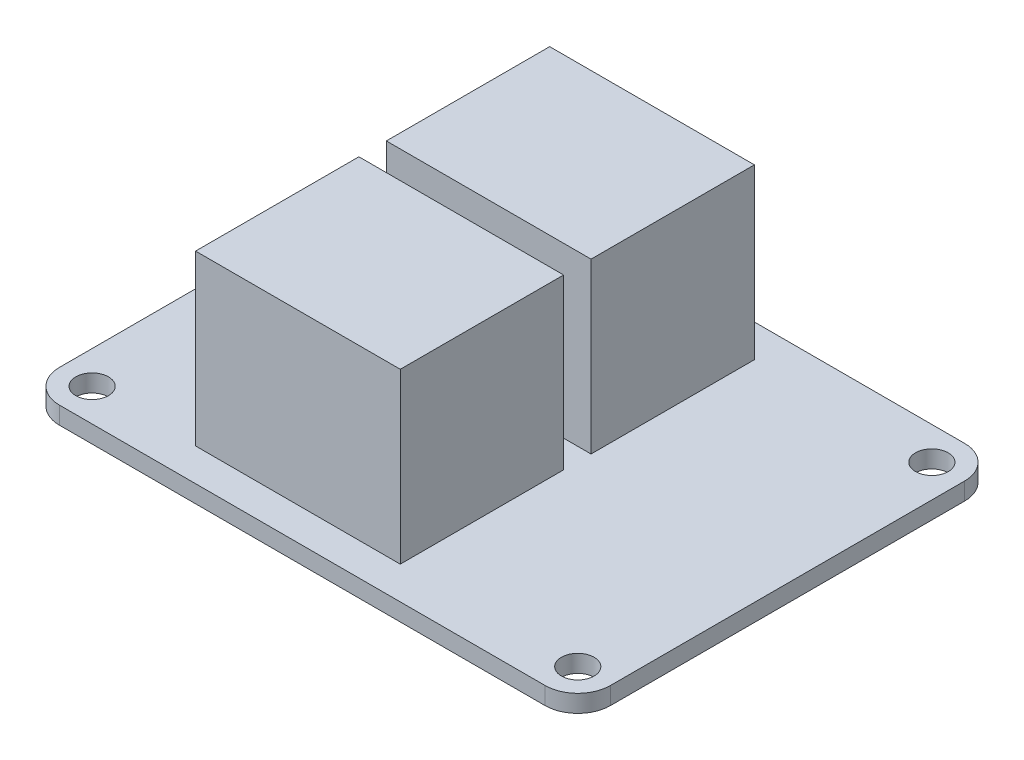
SolidWorks part; units mm, degrees
ref_plane "Front Plane" through (0, 0, 0) normal (0, 0, 1) x (1, 0, 0)
ref_plane "Top Plane" through (0, 0, 0) normal (0, 1, 0) x (1, 0, 0)
ref_plane "Right Plane" through (0, 0, 0) normal (1, 0, 0) x (0, 0, -1)
sketch "Sketch1" plane through (0, 0, 0) normal (0, 1, 0) x (1, 0, 0)
  line L1 (-33.69, 15.154) -> (16.91, 15.154)
  line L2 (-33.69, 15.154) -> (-33.69, -23.366)
  line L3 (-33.69, -23.366) -> (16.91, -23.366)
  line L4 (16.91, 15.154) -> (16.91, -23.366)
  circle A0 centre (13.91, 12.154) radius 1.5
  circle A1 centre (13.91, -20.366) radius 1.5
  circle A2 centre (-30.69, -20.366) radius 1.5
  circle A3 centre (-30.69, 12.154) radius 1.5
  dimension "D3" = 3
  dimension "D4" = 3
  dimension "D5" = 3
  dimension "D6" = 3
  dimension "D7" = 3
  dimension "D8" = 3
  dimension "D9" = 3
  dimension "D10" = 3
  dimension "D11" = 3
  dimension "D12" = 3
  dimension "D13" = 3
  dimension "D14" = 3
  dimension "D1" = 50.6
  dimension "D2" = 38.52
extrude "Boss-Extrude1" add sketch "Sketch1" along normal blind 1.6
fillet "Fillet1" radius 3 1 edges at (16.91, 0.8, -15.154)
fillet "Fillet2" radius 3 1 edges at (-33.69, 0.8, -15.154)
fillet "Fillet3" radius 3 1 edges at (-33.69, 0.8, 23.366)
fillet "Fillet4" radius 3 1 edges at (16.91, 0.8, 23.366)
sketch "Sketch2" plane through (0, 1.6, 0) normal (0, 1, 0) x (1, 0, 0)
  line L0 (13.91, 15.154) -> (-30.69, 15.154) construction
  line L1 (-21.19, 12.154) -> (-2.39, 12.154)
  line L2 (-21.19, 12.154) -> (-21.19, -2.846)
  line L3 (-21.19, -2.846) -> (-2.39, -2.846)
  line L4 (-2.39, 12.154) -> (-2.39, -2.846)
  line L5 (-33.69, 12.154) -> (-33.69, -20.366) construction
  line L6 (-30.69, -23.366) -> (13.91, -23.366) construction
  line L7 (-21.19, -5.366) -> (-2.39, -5.366)
  line L8 (-21.19, -5.366) -> (-21.19, -20.366)
  line L9 (-21.19, -20.366) -> (-2.39, -20.366)
  line L10 (-2.39, -5.366) -> (-2.39, -20.366)
  dimension "D1" = 15
  dimension "D2" = 18.8
  dimension "D3" = 3
  dimension "D4" = 12.5
  dimension "D5" = 15
  dimension "D6" = 18.8
  dimension "D7" = 3
  dimension "D8" = 12.5
extrude "Boss-Extrude2" add sketch "Sketch2" along normal blind 15.5
